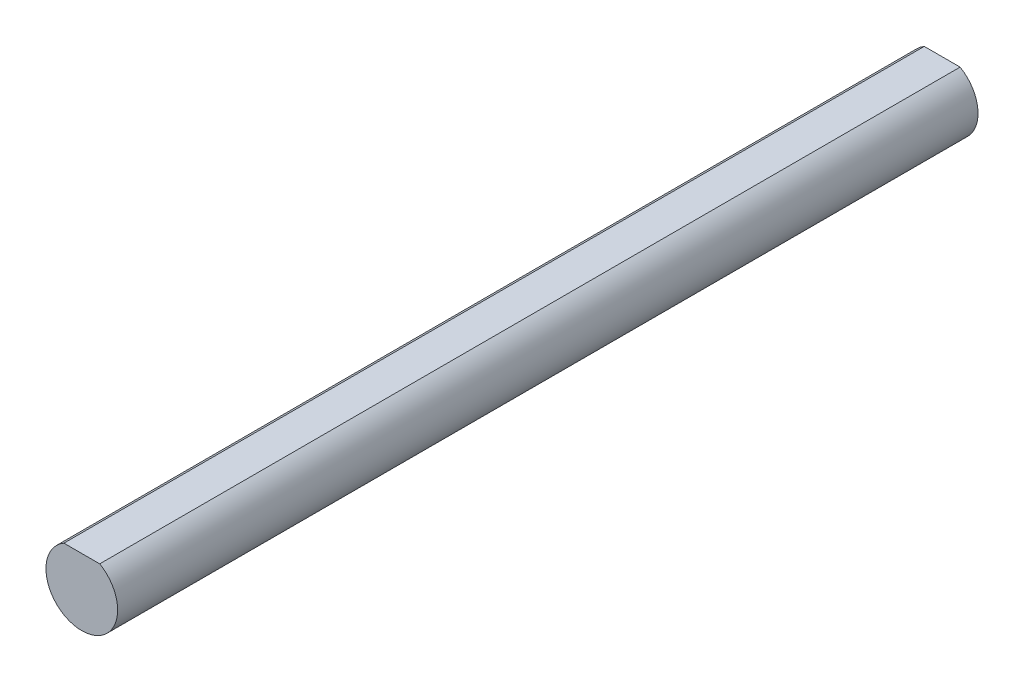
SolidWorks part; units mm, degrees
ref_plane "Front Plane" through (0, 0, 0) normal (0, 0, 1) x (1, 0, 0)
ref_plane "Top Plane" through (0, 0, 0) normal (0, 1, 0) x (1, 0, 0)
ref_plane "Right Plane" through (0, 0, 0) normal (1, 0, 0) x (0, 0, -1)
sketch "Sketch1" plane through (0, 0, 0) normal (0, 0, 1) x (1, 0, 0)
  line L0 (-1.5875, 2.7496) -> (1.5875, 2.7496)
  arc A0 (-1.5875, 2.7496) -> (1.5875, 2.7496) centre (0, 0) ccw
  dimension "D1" = 6.35
  dimension "D2" = 3.175
extrude "Boss-Extrude1" add sketch "Sketch1" along normal mid plane 76.2
